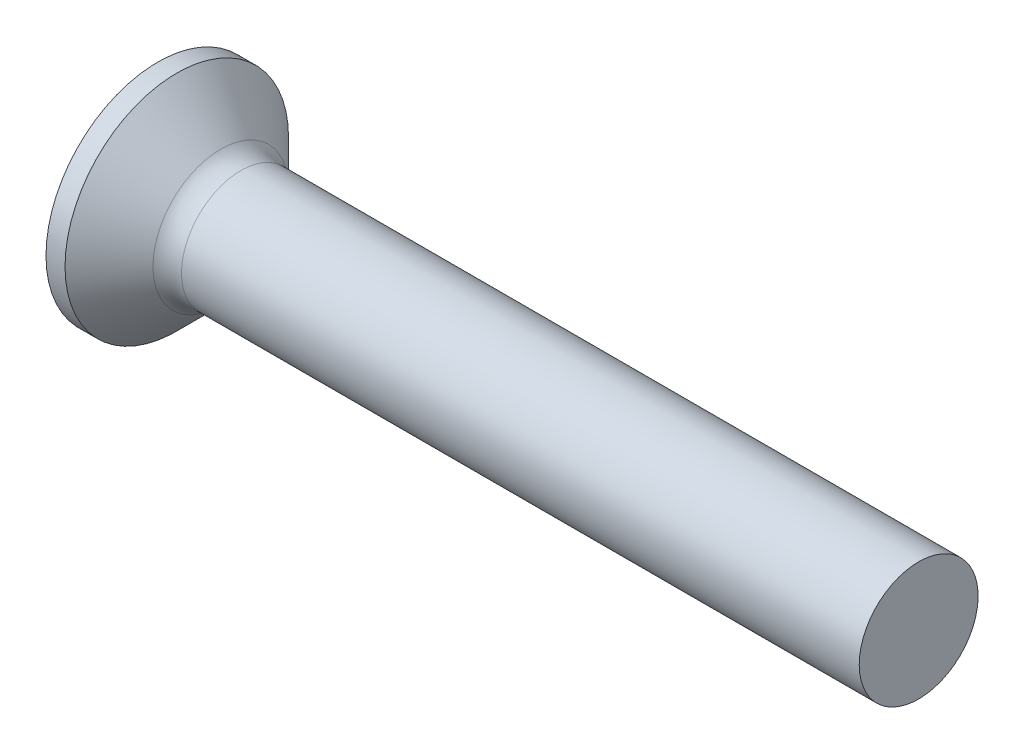
SolidWorks part; units mm, degrees
revolve "Base-Revolve" add sketch "BodySke"
sketch "BodySke" plane through (0, 0, 0) normal (0, 0, 1) x (1, 0, 0)
  line L0 (0, 0) -> (0, 2.35)
  line L1 (0, 2.35) -> (0.4, 2.35)
  line L2 (1.5, 1.25) -> (16, 1.25)
  line L3 (16, 1.25) -> (16, 0)
  line L4 (16, 0) -> (0, 0)
  line L5 (-6.35, 0) -> (82.55, 0) construction
  line L6 (1.5, -1.25) -> (16, -1.25) construction
  line L7 (0.4, -2.35) -> (1.5, -1.25) construction
  line L8 (0.4, 2.35) -> (1.5, 1.25)
  line L9 (0, -2.35) -> (0.4, -2.35) construction
  line L10 (1.95, 2.8375) -> (1.95, -6.6875) construction
  line L11 (0, 6.35) -> (0, -3.175) construction
  dimension "Diameter" = 2.5
  dimension "Length" = 16
  dimension "Head_ht" = 1.5
  dimension "Head_dia" = 4.7
  dimension "Head_ang" = 90
  dimension "D6" = 0.4
  dimension "Advance" = 0.45
  dimension "Thread_nom" = 16
cosmetic thread "ThreadCosmetic" [suppressed]
fillet "Fillet1" radius 0.6 1 edges at (1.5, 0, 1.25)
ref_plane "Plane1" through (0, 0, 0) normal (0, 0, 1) x (1, 0, 0)
ref_plane "Plane2" through (0, 0, 0) normal (0, 1, 0) x (1, 0, 0)
ref_plane "Plane3" through (0, 0, 0) normal (1, 0, 0) x (0, 0, -1)
sketch "Sketch3" plane through (0, 0, 0) normal (-1, 0, 0) x (0, 0, 1)
  line L0 (-0.37, 1.4) -> (0.37, 1.4)
  line L1 (0.37, 1.4) -> (0.37, -1.4)
  line L2 (0.37, -1.4) -> (-0.37, -1.4)
  line L3 (-0.37, -1.4) -> (-0.37, 1.4)
  dimension "Cross_dia" = 2.8
  dimension "Cross_width" = 0.74
  dimension "D1" = 1.4
  dimension "D2" = 0.37
ref_plane "Plane4" through (1.73, 0, 0) normal (-1, 0, 0) x (0, 0, 1)
sketch "Sketch4" plane through (1.73, 0, 0) normal (-1, 0, 0) x (0, 0, 1)
  line L0 (-0.37, 0.5375) -> (0.37, 0.5375)
  line L3 (0.37, 0.5375) -> (0.37, -0.5375)
  line L4 (0.37, -0.5375) -> (-0.37, -0.5375)
  line L5 (-0.37, -0.5375) -> (-0.37, 0.5375)
  dimension "D2" = 1.0749
  dimension "D1" = 0.74
  dimension "D4" = 0.5375
  dimension "D3" = 0.37
loft "Recess" cut profiles "Sketch3", "Sketch4"
pattern_circular "RecPat" count 2 every 90 about axis through (0, 0, 0) along (1, 0, 0) of "Recess"
sketch "RecCorSke" plane through (0, 0, 0) normal (0, 0, 1) x (1, 0, 0)
  line L0 (-3.175, 0) -> (15.875, 0) construction
  line L2 (0, 0) -> (0, 0.677)
  line L3 (0, 0.677) -> (1.73, 0.556)
  line L4 (1.73, 0.556) -> (1.9107, 0)
  line L5 (1.9107, 0) -> (0, 0)
  dimension "Diameter" = 1.112
  dimension "Depth" = 1.73
  dimension "Draft_angle" = 4
  dimension "Bottom_angle" = 18
revolve "RecessCore" cut sketch "RecCorSke" angle 360 about L0
sketch "ThdSchSke" plane through (0, 0, 0) normal (0, 0, 1) x (1, 0, 0)
  line L0 (1.95, -0.9965) -> (1.7725, -1.25)
  line L1 (1.95, -0.9965) -> (2.1275, -1.25)
  line L2 (2.1275, -1.25) -> (2.1275, -1.5625)
  line L3 (-3.175, 0) -> (5.1513, 0) construction
  line L5 (2.1275, -1.5625) -> (1.7725, -1.5625)
  line L6 (1.7725, -1.5625) -> (1.7725, -1.25)
  line L7 (0, 2.35) -> (0, -2.35) construction
  dimension "Diameter" = 2.5
  dimension "Thread_minor" = 1.993
  dimension "Start" = 1.95
revolve "ThreadSchematic" [suppressed] cut sketch "ThdSchSke" angle 360 about L3
pattern_linear "ThdSchPat" [suppressed]
equation "\"D1@Sketch3\" = \"Cross_dia@Sketch3\" / 2"
equation "\"D2@Sketch3\" = \"Cross_width@Sketch3\" / 2"
equation "\"Depth@RecCorSke\" = \"Cross_depth@Plane4\""
equation "\"D1@Sketch4\" = \"Cross_width@Sketch3\""
equation "\"D2@Sketch4\" = \"Cross_dia@Sketch3\" - 2.0 * \"Cross_depth@Plane4\" * tan(26.5  * 0.017453292)"
equation "\"D3@Sketch4\" = \"D1@Sketch4\" / 2"
equation "\"D4@Sketch4\" = \"D2@Sketch4\" / 2"
equation "\"Thread_length@ThreadCosmetic\" = ((sgn( (\"Length@BodySke\" - \"Advance@BodySke\" * 1.0 - \"Head_ht@BodySke\" ) - \"Thread_nom@BodySke\" )-1)*( (\"Length@BodySke\" - \"Advance@BodySke\" * 1.0 - \"Head_ht@BodySke\" ) - \"Thread_nom@BodySke\" ))/-2+ \"Thread_nom@BodySke\""
equation "\"Thread_minor@ThdSchSke\" = \"Thread_minor@ThreadCosmetic\""
equation "\"Diameter@ThdSchSke\" = \"Diameter@BodySke\""
equation "\"Overcut@ThdSchSke\" = \"Diameter@BodySke\" * 1.25"
equation "\"Start@ThdSchSke\" = 0.000001 + \"Length@BodySke\" - \"Thread_length@ThreadCosmetic\"  '---Countersunk---"
equation "\"Num_threads@ThdSchPat\" = int( \"Thread_length@ThreadCosmetic\" / \"Advance@BodySke\" + 0.999 )  + 1"
equation "\"Advance@ThdSchPat\" = \"Thread_length@ThreadCosmetic\" /  (\"Num_threads@ThdSchPat\" - 1) 'relax it"
